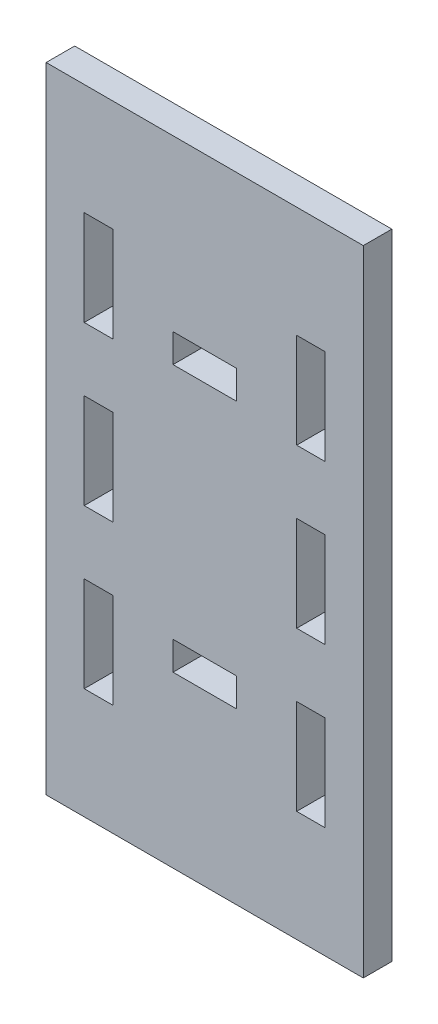
SolidWorks part; units mm, degrees
ref_plane "Front Plane" through (0, 0, 0) normal (0, 0, 1) x (1, 0, 0)
ref_plane "Top Plane" through (0, 0, 0) normal (0, 1, 0) x (1, 0, 0)
ref_plane "Right Plane" through (0, 0, 0) normal (1, 0, 0) x (0, 0, -1)
sketch "Model" plane through (0, 0, 0) normal (0, 0, 1) x (1, 0, 0)
  line L20 (50, 0) -> (50, 200) construction
  line L21 (0, 200) -> (100, 200)
  line L22 (0, 200) -> (0, 0)
  line L23 (0, 0) -> (100, 0)
  line L24 (100, 200) -> (100, 0)
  line L25 (0, 100) -> (100, 100) construction
  line L26 (40, 53.5) -> (60, 53.5)
  line L27 (40, 137.5) -> (60, 137.5)
  line L28 (40, 137.5) -> (40, 146.5)
  line L29 (40, 146.5) -> (60, 146.5)
  line L30 (60, 137.5) -> (60, 146.5)
  line L31 (40, 137.5) -> (60, 146.5) construction
  line L32 (40, 146.5) -> (60, 137.5) construction
  line L33 (40, 62.5) -> (40, 53.5)
  line L34 (60, 62.5) -> (60, 53.5)
  line L35 (40, 62.5) -> (60, 62.5)
  line L36 (12, 165) -> (21, 165)
  line L37 (12, 85) -> (21, 85)
  line L38 (12, 85) -> (12, 115)
  line L39 (12, 115) -> (21, 115)
  line L40 (21, 85) -> (21, 115)
  line L41 (12, 85) -> (21, 115) construction
  line L42 (12, 115) -> (21, 85) construction
  line L43 (21, 135) -> (21, 165)
  line L44 (12, 135) -> (21, 135)
  line L45 (12, 135) -> (12, 165)
  line L46 (21, 35) -> (21, 65)
  line L47 (12, 65) -> (21, 65)
  line L48 (12, 35) -> (12, 65)
  line L49 (12, 35) -> (21, 35)
  line L50 (88, 35) -> (79, 35)
  line L51 (88, 35) -> (88, 65)
  line L52 (79, 35) -> (79, 65)
  line L53 (88, 65) -> (79, 65)
  line L54 (88, 85) -> (79, 85)
  line L55 (79, 85) -> (79, 115)
  line L78 (88, 85) -> (88, 115)
  line L79 (88, 115) -> (79, 115)
  line L80 (79, 135) -> (79, 165)
  line L81 (88, 135) -> (88, 165)
  line L82 (88, 165) -> (79, 165)
  line L83 (88, 135) -> (79, 135)
  point P0 (50, 100)
  point P50 (50, 142)
  point P59 (16.5, 100)
  dimension "D9" = 200
  dimension "D10" = 100
  dimension "D11" = 9
  dimension "D12" = 20
  dimension "D13" = 9
  dimension "D14" = 30
  dimension "D4" = 20
  dimension "D18" = 20
  dimension "D2" = 58
  dimension "D3" = 42
  dimension "D16" = 2
  dimension "D17" = 2
extrude "Boss-Extrude1" add sketch "Model" along normal blind 9
equation "\"material-thickness\" = 9mm"
equation "\"linear-bar-bearingouter-dia\" = 15mm ' Diameter of the outer side of the bearing"
equation "\"tab-width-small\" = 20mm ' Width of the small version of the Tab"
equation "\"tab-width-large\" = 30mm ' Width of the large version of the Tab"
equation "\"xplate-width\" = 100mm"
equation "\"xplate-height\" = 200mm"
equation "\"plate-supporttab-gapwidth\" = 40mm"
equation "\"plate-supporttab-gapheight\" = 20mm"
equation "\"vert-gap-distance\"= ( ( 70 - 16 - 30 ) / 2 ) + 30"
equation "\"D1@Boss-Extrude1\"=\"material-thickness\""
equation "\"D11@Model\"=\"material-thickness\""
equation "\"D13@Model\"=\"material-thickness\""
equation "\"D12@Model\"=\"tab-width-small\""
equation "\"D14@Model\"=\"tab-width-large\""
equation "\"D10@Model\"=\"xplate-width\""
equation "\"D9@Model\"=\"xplate-height\""
equation "\"D2@Model\"=\"plate-supporttab-gapwidth\"+(\"material-thickness\" * 2)"
equation "\"D4@Model\"=\"plate-supporttab-gapheight\""
equation "\"D18@Model\"=\"plate-supporttab-gapheight\""
equation "\"D3@Model\"=\"vert-gap-distance\""
